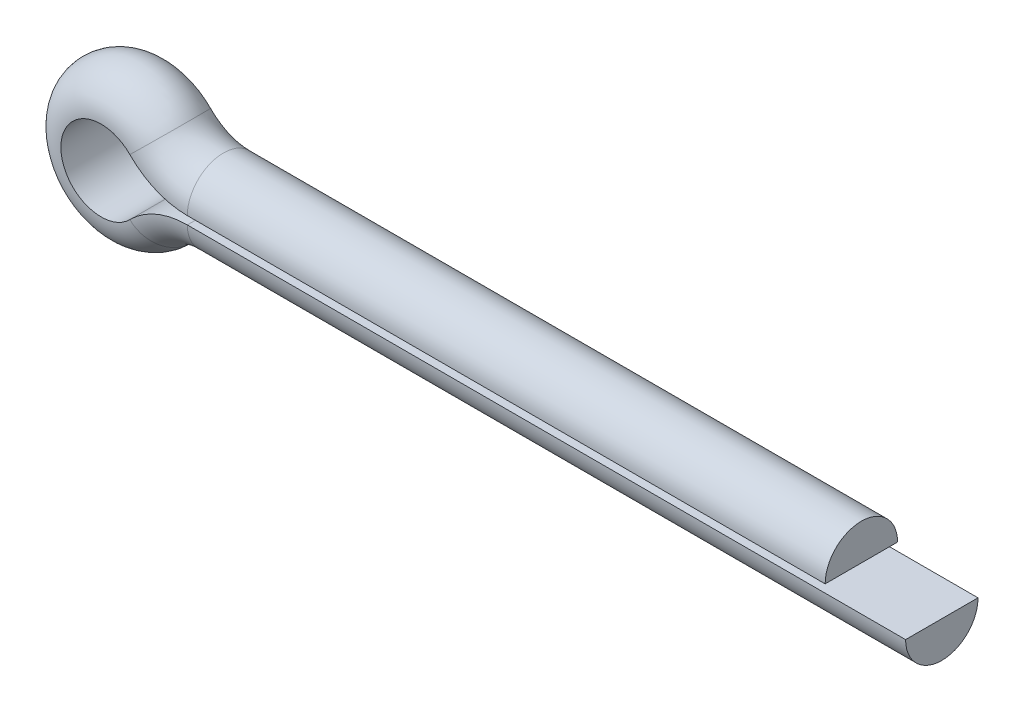
SolidWorks part; units mm, degrees
ref_plane "前基準面" through (0, 0, 0) normal (0, 0, 1) x (1, 0, 0)
ref_plane "上基準面" through (0, 0, 0) normal (0, 1, 0) x (1, 0, 0)
ref_plane "右基準面" through (0, 0, 0) normal (1, 0, 0) x (0, 0, -1)
sketch "草圖1" plane through (0, 0, 0) normal (0, 0, 1) x (1, 0, 0)
  line L0 (18, 0.1) -> (2.1424, 0.1)
  line L1 (0, 0) -> (12.3929, 0) construction
  line L2 (2.1424, -0.1) -> (20, -0.1)
  arc A0 (0.7141, 0.7) -> (0.7141, -0.7) centre (0, 0) ccw
  arc A1 (2.1424, 0.1) -> (0.7141, 0.7) centre (2.1424, 2.1) cw
  arc A2 (2.1424, -0.1) -> (0.7141, -0.7) centre (2.1424, -2.1) ccw
  dimension "D1" = 1
  dimension "D3" = 18
  dimension "D4" = 2
  dimension "D5" = 20
  dimension "D2" = 0.2
ref_plane "平面1" through (18, 0.1, 0) normal (-1, 0, 0) x (0, 0, 1)
sketch "草圖2" plane through (18, 0.1, 0) normal (-1, 0, 0) x (0, 0, 1)
  line L0 (-0.9, 0) -> (0.9, 0)
  arc A0 (0.9, 0) -> (-0.9, 0) centre (0, 0) ccw
  dimension "D1" = 0.9
sweep "掃出1" add profiles "草圖2" path "草圖1"
